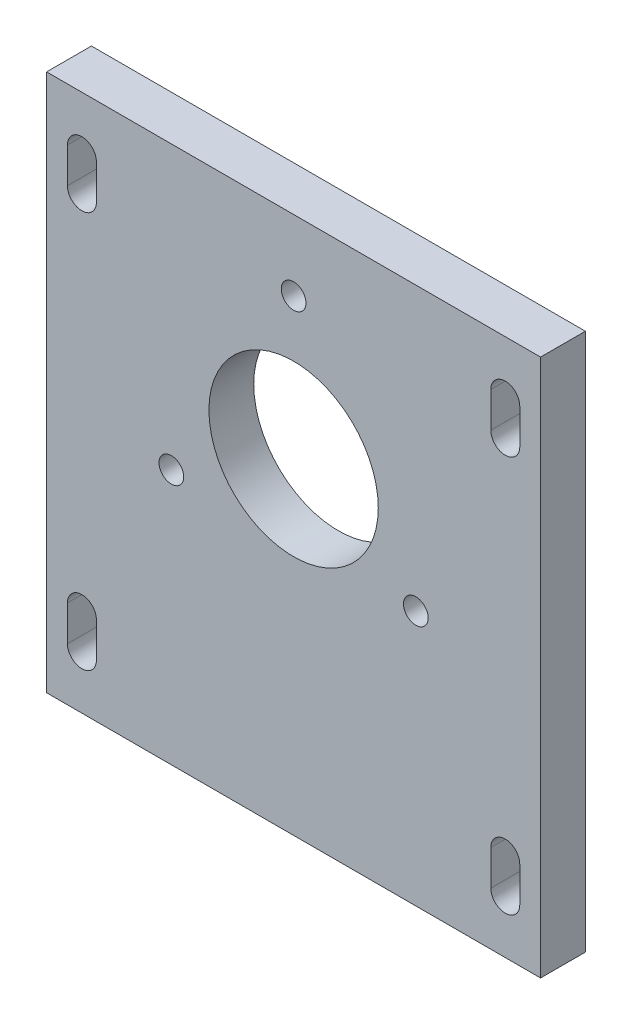
SolidWorks part; units mm, degrees
ref_plane "Front Plane" through (0, 0, 0) normal (0, 0, 1) x (1, 0, 0)
ref_plane "Top Plane" through (0, 0, 0) normal (0, 1, 0) x (1, 0, 0)
ref_plane "Right Plane" through (0, 0, 0) normal (1, 0, 0) x (0, 0, -1)
sketch "Sketch1" plane through (0, 0, 0) normal (0, 0, 1) x (1, 0, 0)
  line L0 (0, 38.1) -> (0, -38.1) construction
  line L1 (-35, -38.1) -> (35, -38.1)
  line L2 (-35, -38.1) -> (-35, 38.1)
  line L3 (-35, 38.1) -> (35, 38.1)
  line L4 (35, -38.1) -> (35, 38.1)
  line L5 (-35, -38.1) -> (35, 38.1) construction
  line L6 (-35, 38.1) -> (35, -38.1) construction
  line L7 (-35, 0) -> (35, 0) construction
  line L8 (-35, 28.1) -> (0, 28.1) construction
  line L9 (-30, 25.6) -> (-30, 30.6) construction
  line L10 (-32.05, 25.6) -> (-32.05, 30.6)
  line L11 (-27.95, 25.6) -> (-27.95, 30.6)
  line L12 (30, 25.6) -> (30, 30.6) construction
  line L13 (32.05, 25.6) -> (32.05, 30.6)
  line L14 (27.95, 25.6) -> (27.95, 30.6)
  line L15 (-30, -25.6) -> (-30, -30.6) construction
  line L16 (-32.05, -25.6) -> (-32.05, -30.6)
  line L17 (-27.95, -25.6) -> (-27.95, -30.6)
  line L18 (30, -25.6) -> (30, -30.6) construction
  line L19 (32.05, -25.6) -> (32.05, -30.6)
  line L20 (27.95, -25.6) -> (27.95, -30.6)
  circle A0 centre (-30, 28.1) radius 2.05 construction
  arc A1 (-32.05, 25.6) -> (-27.95, 25.6) centre (-30, 25.6) ccw
  arc A2 (-27.95, 30.6) -> (-32.05, 30.6) centre (-30, 30.6) ccw
  arc A3 (32.05, 25.6) -> (27.95, 25.6) centre (30, 25.6) cw
  arc A4 (27.95, 30.6) -> (32.05, 30.6) centre (30, 30.6) cw
  arc A5 (-32.05, -25.6) -> (-27.95, -25.6) centre (-30, -25.6) cw
  arc A6 (-27.95, -30.6) -> (-32.05, -30.6) centre (-30, -30.6) cw
  arc A7 (32.05, -25.6) -> (27.95, -25.6) centre (30, -25.6) ccw
  arc A8 (27.95, -30.6) -> (32.05, -30.6) centre (30, -30.6) ccw
  circle A10 centre (0, 8.1) radius 20 construction
  circle A11 centre (0, 28.1) radius 1.75
  circle A12 centre (17.3205, -1.9) radius 1.75
  circle A13 centre (-17.3205, -1.9) radius 1.75
  circle A14 centre (0, 8.1) radius 12
  circle A15 centre (0, 8.1) radius 33.35 construction
  point P0 (0, 0)
  point P16 (-30, 28.1)
  point P24 (30, 28.1)
  point P31 (-30, -28.1)
  point P38 (30, -28.1)
  point P46 (-20.828, 28.4132)
  point P52 (0, 8.1)
  dimension "D4" = 4.1
  dimension "D6" = 2.05
  dimension "D7" = 40
  dimension "D9" = 3.5
  dimension "D11" = 24
  dimension "D12" = 66.7
  dimension "D1" = 76.2
  dimension "D2" = 70
  dimension "D3" = 10
  dimension "D5" = 5
  dimension "D8" = 46.2
  dimension "D13" = 5
  dimension "D10" = 3
extrude "Boss-Extrude1" add sketch "Sketch1" along normal blind 6.35
